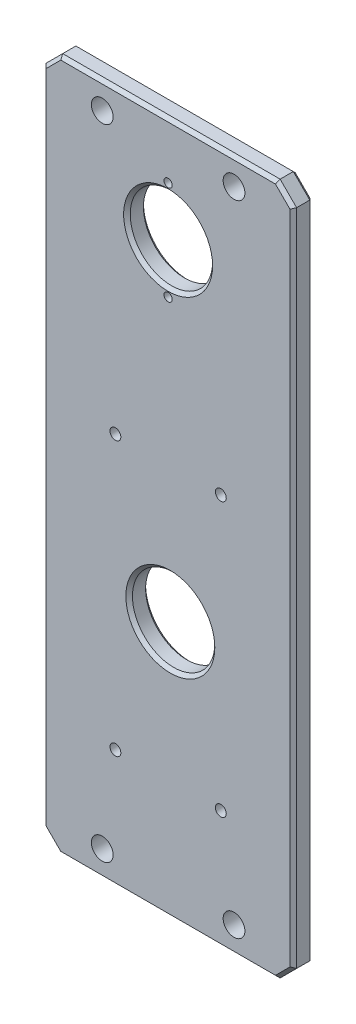
SolidWorks part; units mm, degrees
ref_plane "前视基准面" through (0, 0, 0) normal (0, 0, 1) x (1, 0, 0)
ref_plane "上视基准面" through (0, 0, 0) normal (0, 1, 0) x (1, 0, 0)
ref_plane "右视基准面" through (0, 0, 0) normal (1, 0, 0) x (0, 0, -1)
sketch "草图1" plane through (0, 0, 0) normal (0, 0, 1) x (1, 0, 0)
  line L1 (-38, 105) -> (38, 105)
  line L2 (-38, 105) -> (-38, -105)
  line L3 (-38, -105) -> (38, -105)
  line L4 (38, 105) -> (38, -105)
  line L5 (-38, 105) -> (38, -105) construction
  line L6 (-38, -105) -> (38, 105) construction
  point P0 (0, 0)
  dimension "D1" = 76
  dimension "D2" = 210
extrude "凸台-拉伸1" add sketch "草图1" along normal blind 6
sketch "草图2" plane through (0, 0, 6) normal (0, 0, 1) x (1, 0, 0)
  line L0 (38, 105) -> (-38, 105) construction
  line L1 (-20, -97) -> (20, -97) construction
  line L2 (-20, -97) -> (-20, 97) construction
  line L3 (-20, 97) -> (20, 97) construction
  line L4 (20, -97) -> (20, 97) construction
  line L5 (-20, -97) -> (20, 97) construction
  line L6 (-20, 97) -> (20, -97) construction
  circle A0 centre (-20, 97) radius 3.3
  circle A1 centre (20, 97) radius 3.3
  circle A2 centre (-20, -97) radius 3.3
  circle A3 centre (20, -97) radius 3.3
  point P0 (0, 0)
  dimension "D3" = 6.6
  dimension "D1" = 40
  dimension "D2" = 8
extrude "切除-拉伸1" cut sketch "草图2" against normal through all
chamfer "倒角2" distance 5 angle 45 4 edges at (-38, -105, 3) (38, -105, 3) (-38, 105, 3) (38, 105, 3)
chamfer "倒角1" distance 1 angle 45 16 edges at (-38, 0, 6) (-35.5, -102.5, 6) (-35.5, 102.5, 6) (0, -105, 6) (0, 105, 6) (35.5, -102.5, 6) (35.5, 102.5, 6) (38, 0, 6) (-38, 0, 0) (-35.5, -102.5, 0) (-35.5, 102.5, 0) (0, -105, 0) (0, 105, 0) (35.5, -102.5, 0) (35.5, 102.5, 0) (38, 0, 0)
hole_wizard "M4 螺纹孔1" positions "草图3" profile "草图4" tap size "M4" standard "GB"
sketch "草图3" plane through (0, 0, 0) normal (0, 0, -1) x (-1, 0, 0)
  point P0 (-16, 14)
  point P4 (16, 14)
  point P7 (16, -69)
  point P10 (-16, -69)
  point P13 (0, 0)
  point P14 (-16, 14)
  point P16 (0, 0)
  point P17 (16.8851, 14.0011)
  point P19 (0, 0)
  point P20 (-16, -69)
  point P22 (0, 0)
  point P23 (16, -69)
  point P25 (0, 0)
  point P26 (16, 14)
  point P28 (0, 0)
  point P29 (-16, 14)
  point P31 (0, 0)
  point P32 (-16, -69)
  point P34 (0, 0)
  point P35 (16, -69)
sketch "草图4" plane through (16, 14, 0) normal (1, 0, 0) x (0, 1, 0)
  line L0 (0, 0) -> (0, 11.0914)
  line L1 (0, 11.0914) -> (1.65, 10.1)
  line L2 (1.65, 10.1) -> (1.65, 0)
  line L5 (1.65, 0) -> (0, 0)
  line L10 (0, 11.0914) -> (-1.65, 10.1) construction
  line L11 (0, -6.35) -> (0, 107.95) construction
  dimension "螺纹孔钻头直径" = 3.3
  dimension "螺纹孔钻头深度" = 10.1
  dimension "导头角度" = 118
cosmetic thread "孔螺蚊线1" parameters "D1"=8, "D2"=4
cosmetic thread "孔螺蚊线2" parameters "D1"=8, "D2"=4
cosmetic thread "孔螺蚊线3" parameters "D1"=8, "D2"=4
cosmetic thread "孔螺蚊线4" parameters "D1"=8, "D2"=4
hole_wizard "M3 螺纹孔1" positions "草图5" profile "草图6" tap size "M3" standard "GB"
sketch "草图5" plane through (0, 0, 0) normal (0, 0, -1) x (-1, 0, 0)
  point P0 (0, 58)
  point P3 (0, 88)
sketch "草图6" plane through (0, 58, 0) normal (1, 0, 0) x (0, 1, 0)
  line L0 (0, 0) -> (0, 8.2511)
  line L1 (0, 8.2511) -> (1.25, 7.5)
  line L2 (1.25, 7.5) -> (1.25, 0)
  line L5 (1.25, 0) -> (0, 0)
  line L10 (0, 8.2511) -> (-1.25, 7.5) construction
  line L11 (0, -6.35) -> (0, 107.95) construction
  dimension "螺纹孔钻头直径" = 2.5
  dimension "螺纹孔钻头深度" = 7.5
  dimension "导头角度" = 118
cosmetic thread "孔螺蚊线5" parameters "D1"=6, "D2"=3
cosmetic thread "孔螺蚊线6" parameters "D1"=6, "D2"=3
sketch "草图7" plane through (0, 0, 0) normal (0, 0, -1) x (-1, 0, 0)
  line L0 (0, 88) -> (0, 58) construction
  circle A0 centre (0, 73) radius 12.5
  dimension "D1" = 25
extrude "切除-拉伸2" cut sketch "草图7" against normal through all
sketch "草图8" plane through (0, 0, 0) normal (0, 0, -1) x (-1, 0, 0)
  line L0 (-17.3414, 14.9608) -> (16, -69) construction
  circle A0 centre (-16, 14) radius 1.65 construction
  circle A1 centre (-0.6707, -27.0196) radius 12.5
  dimension "D1" = 25
extrude "切除-拉伸3" cut sketch "草图8" against normal through all
chamfer "倒角3" distance 1 angle 45 4 edges at (-12.5, 73, 6) (-12.5, 73, 0) (-11.8293, -27.0196, 6) (-11.8293, -27.0196, 0)
